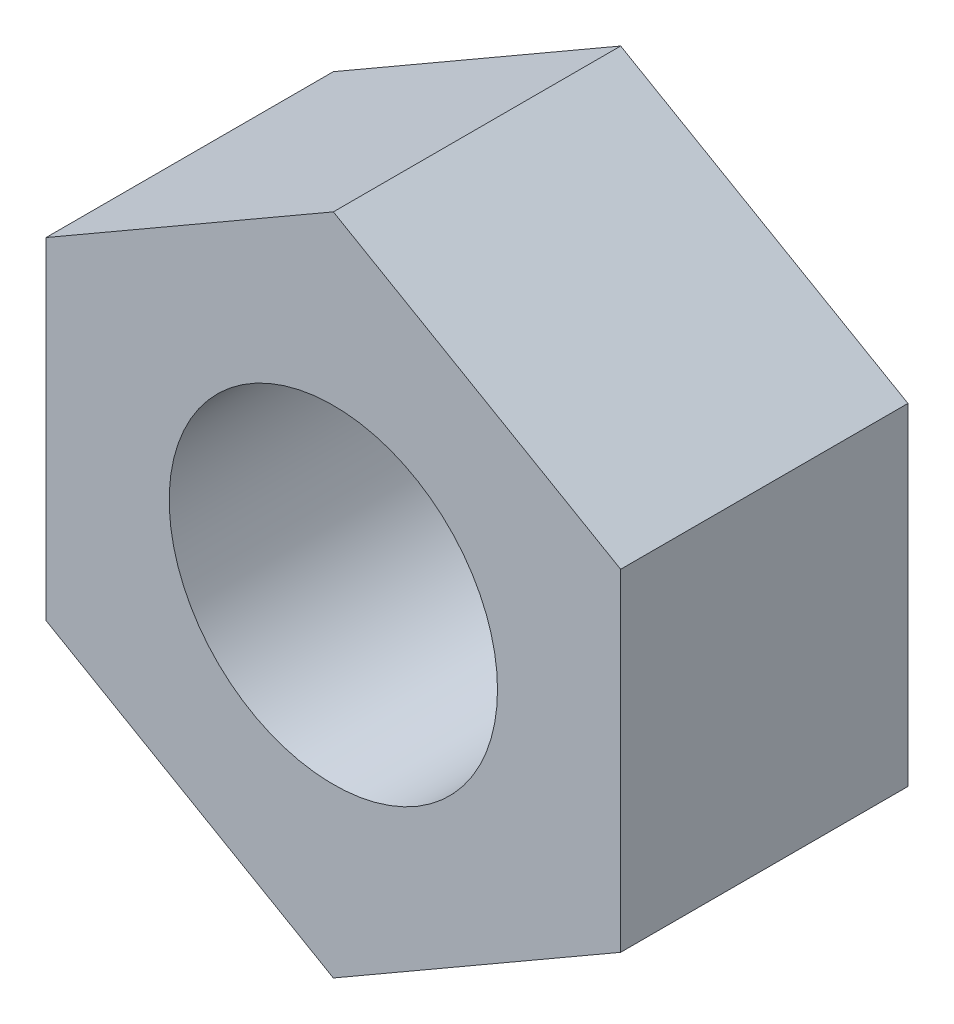
SolidWorks part; units mm, degrees
ref_plane "Front" through (0, 0, 0) normal (0, 0, 1) x (1, 0, 0)
ref_plane "Top" through (0, 0, 0) normal (0, 1, 0) x (1, 0, 0)
ref_plane "Right" through (0, 0, 0) normal (1, 0, 0) x (0, 0, -1)
sketch "Sketch1" plane through (0, 0, 0) normal (0, 0, 1) x (1, 0, 0)
  line L1 (-5.5562, 3.2079) -> (-5.5562, -3.2079)
  line L2 (-5.5562, -3.2079) -> (0, -6.4158)
  line L3 (0, -6.4158) -> (5.5562, -3.2079)
  line L4 (5.5562, -3.2079) -> (5.5562, 3.2079)
  line L5 (5.5562, 3.2079) -> (0, 6.4158)
  line L6 (0, 6.4158) -> (-5.5562, 3.2079)
  circle A0 centre (0, 0) radius 5.5562 construction
  circle A1 centre (0, 0) radius 3.175
  point P10 (0, 3.175)
  dimension "hex" = 11.1125
  dimension "dia" = 6.35
extrude "Extrude1" add sketch "Sketch1" along normal mid plane 5.5562
sketch "Sketch4" plane through (0, 0, -2.7781) normal (0, 0, -1) x (-1, 0, 0)
  circle A0 centre (0, 0) radius 3.175 construction
  circle A1 centre (0, 0) radius 3.175
curve "Helix/Spiral3" pitch 1.27 height 6.6675 turns 5.25
equation "\"D3@Helix/Spiral3\" = \"length@Extrude1\" * 1.2"
equation "\"D2@Sketch3\" = \"D4@Helix/Spiral3\" * .5"
equation "\"D3@Sketch3\" = \"D4@Helix/Spiral3\" * .125"
equation "\"D2@Sketch6\" = \"D4@Helix/Spiral3\" * .5"
